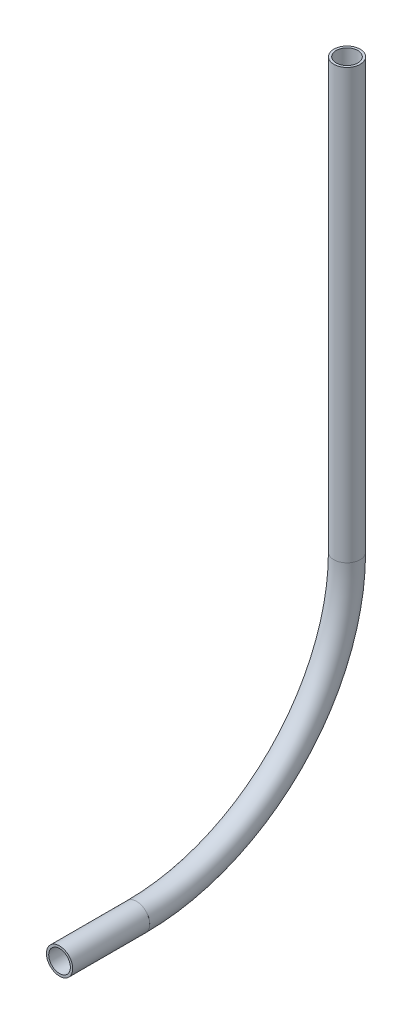
SolidWorks part; units mm, degrees
ref_plane "Front Plane" through (0, 0, 0) normal (0, 0, 1) x (1, 0, 0)
ref_plane "Top Plane" through (0, 0, 0) normal (0, 1, 0) x (1, 0, 0)
ref_plane "Right Plane" through (0, 0, 0) normal (1, 0, 0) x (0, 0, -1)
sketch "Sketch1" plane through (0, 0, 0) normal (1, 0, 0) x (0, 0, -1)
  line L0 (-303.1646, 598.0645) -> (-284.5574, 598.0645)
  line L1 (-233.7574, 648.8645) -> (-233.7574, 752.4586)
  arc A0 (-284.5574, 598.0645) -> (-233.7574, 648.8645) centre (-284.5574, 648.8645) ccw
  point P2 (-284.5574, 598.0645)
  dimension "D1" = 50.8
other "Pipe 0.5 SCH 40(1)"
ref_plane "Plane1" through (0, 598.0645, 303.1646) normal (0, 0, -1) x (0, 1, 0)
sketch "Sketch11" plane through (0, 598.0645, 303.1646) normal (0, 0, -1) x (0, 1, 0)
  circle A0 centre (0, 0) radius 3.175
  circle A1 centre (0, 0) radius 2.6162
  point P5 (0, 0)
  dimension "In_dia" = 6.35
  dimension "Out_dia" = 5.2324
